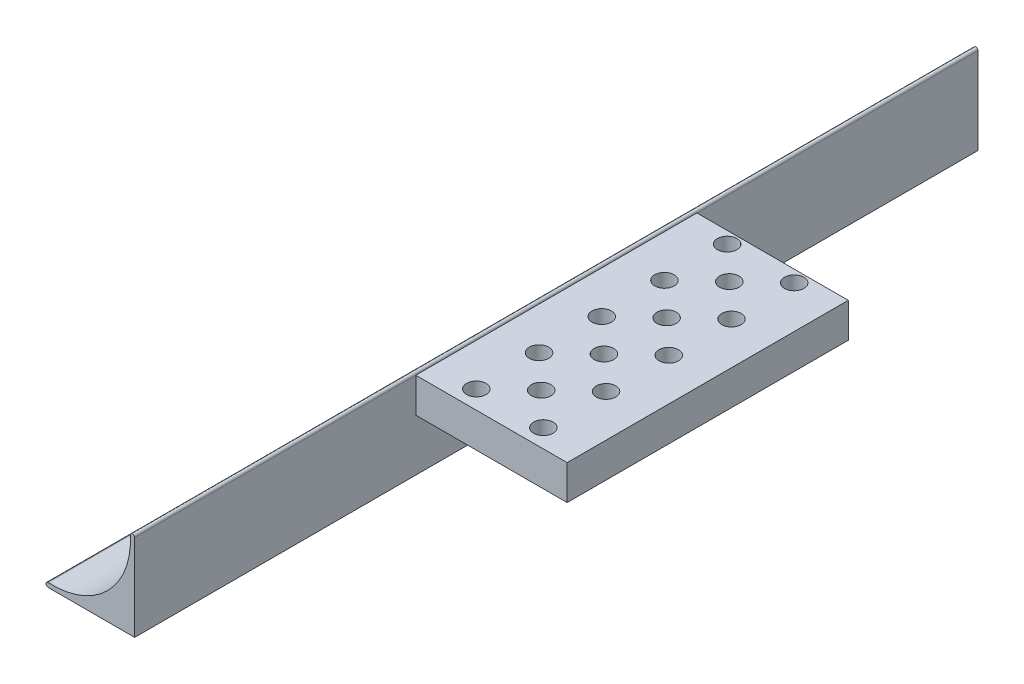
SolidWorks part; units mm, degrees
ref_plane "Alzado" through (0, 0, 0) normal (0, 0, 1) x (1, 0, 0)
ref_plane "Planta" through (0, 0, 0) normal (0, 1, 0) x (1, 0, 0)
ref_plane "Vista lateral" through (0, 0, 0) normal (1, 0, 0) x (0, 0, -1)
sketch "Croquis1" plane through (0, 0, 0) normal (0, 0, 1) x (1, 0, 0)
  line L0 (-20, 0) -> (0, 0)
  line L1 (0, 0) -> (0, 20)
  arc A1 (0, 20) -> (-0.9992, 19.9722) centre (-0.5, 20) ccw
  arc A2 (-19.9722, 0.9992) -> (-20, 0) centre (-20, 0.5) ccw
  arc A3 (-19.9722, 0.9992) -> (-0.9992, 19.9722) centre (-18.9714, 18.9714) ccw
  point P7 (0, 20)
  point P11 (-18.8063, 18.8063)
  dimension "D3" = 1
  dimension "D4" = 1
  dimension "D5" = 36
  dimension "D1" = 20
  dimension "D2" = 20
extrude "Saliente-Extruir1" add sketch "Croquis1" along normal mid plane 195
sketch "Croquis2" plane through (0, 0, 0) normal (1, 0, 0) x (0, 0, -1)
  line L1 (-32.5, 20) -> (32.5, 20)
  line L2 (-32.5, 20) -> (-32.5, 12)
  line L3 (-32.5, 12) -> (32.5, 12)
  line L4 (32.5, 20) -> (32.5, 12)
  line L5 (-97.5, 20) -> (97.5, 20) construction
  point P6 (0, 12)
  dimension "D1" = 8
  dimension "D2" = 65
extrude "Saliente-Extruir2" add sketch "Croquis2" along normal blind 35
hole_wizard "Taladro de margen para M41" positions "Croquis3" profile "Croquis4" hole size "M4" standard "DIN" end condition through all
sketch "Croquis3" plane through (0, 12, 0) normal (0, -1, 0) x (-1, 0, 0)
  line L0 (-6.75, -28.25) -> (-12.75, -28.25) construction
  line L2 (-9.75, -30.25) -> (-9.75, -26.25) construction
  line L3 (-8.75, -30.25) -> (-10.75, -30.25) construction
  line L4 (-10.75, -26.25) -> (-8.75, -26.25) construction
  line L6 (-25.25, -30.25) -> (-25.25, 31.75) construction
  line L7 (-24.25, -30.25) -> (-26.25, -30.25) construction
  line L8 (-26.25, 31.75) -> (-24.25, 31.75) construction
  line L10 (-9.75, -30.25) -> (-9.75, 31.75) construction
  line L11 (-10.75, 31.75) -> (-8.75, 31.75) construction
  line L13 (-17.5, -23) -> (-17.5, 24.5) construction
  line L14 (-16.5, -23) -> (-18.5, -23) construction
  line L15 (-18.5, 24.5) -> (-16.5, 24.5) construction
  line L16 (-6.75, -28.25) -> (-28.25, -28.25) construction
  line L18 (-6.75, -21) -> (-28.25, -21) construction
  line L19 (-6.75, -13.75) -> (-28.25, -13.75) construction
  line L20 (-6.75, -6.5) -> (-28.25, -6.5) construction
  line L21 (-6.75, 0.75) -> (-28.25, 0.75) construction
  line L22 (-6.75, 8) -> (-28.25, 8) construction
  line L23 (-6.75, 15.25) -> (-28.25, 15.25) construction
  line L24 (-6.75, 22.5) -> (-28.25, 22.5) construction
  line L25 (-6.75, 29.75) -> (-28.25, 29.75) construction
  arc A0 (-8.75, -30.25) -> (-8.75, -26.25) centre (-8.75, -28.25) ccw construction
  arc A1 (-10.75, -26.25) -> (-10.75, -30.25) centre (-10.75, -28.25) ccw construction
  arc A2 (-26.25, -26.25) -> (-26.25, -30.25) centre (-26.25, -28.25) ccw construction
  point P25 (-9.75, -28.25)
  point P112 (-25.25, -28.25)
  point P114 (-25.25, -13.75)
  point P116 (-17.5, -21)
  point P118 (-9.75, -13.75)
  point P120 (-9.75, 0.75)
  point P122 (-25.25, 0.75)
  point P124 (-17.5, -6.5)
  point P126 (-17.5, 8)
  point P128 (-9.75, 15.25)
  point P130 (-25.25, 15.25)
  point P132 (-9.75, 29.75)
  point P134 (-17.5, 22.5)
  point P136 (-25.25, 29.75)
  point P137 (0, 0)
  point P140 (0, 0)
  point P141 (0, 0)
  point P142 (0, 0)
  point P143 (0, 0)
  point P144 (0, 0)
  point P145 (0, 0)
  point P146 (0, 0)
  point P147 (0, 0)
  dimension "D1" = 9
sketch "Croquis4" plane through (9.75, 12, 28.25) normal (1, 0, 0) x (0, 0, -1)
  line L0 (0, 0) -> (0, 8.5)
  line L1 (0, 8.5) -> (2.25, 8.5)
  line L2 (2.25, 8.5) -> (2.25, 0.025)
  line L3 (2.25, 0.025) -> (2.275, 0)
  line L5 (2.275, 0) -> (0, 0)
  line L6 (-2.25, 0.025) -> (-2.275, 0) construction
  line L11 (0, -6.35) -> (0, 107.95) construction
  dimension "Diámetro de taladro hasta el siguiente" = 4.5
  dimension "Profundidad de taladro hasta el siguiente" = 8.5
  dimension "Diámetro de avellanado cercano" = 4.55
  dimension "Ángulo de avellanado cercano" = 90
